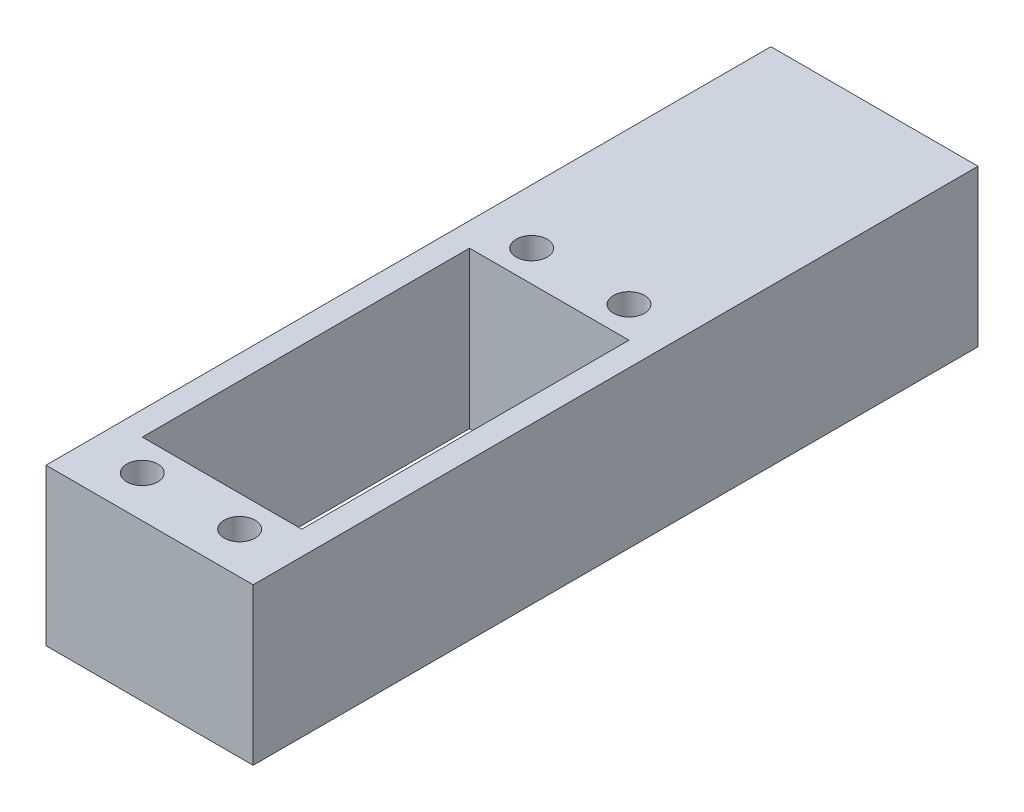
SolidWorks part; units mm, degrees
ref_plane "Front Plane" through (0, 0, 0) normal (0, 0, 1) x (1, 0, 0)
ref_plane "Top Plane" through (0, 0, 0) normal (0, 1, 0) x (1, 0, 0)
ref_plane "Right Plane" through (0, 0, 0) normal (1, 0, 0) x (0, 0, -1)
sketch "Sketch1" plane through (0, 0, 0) normal (0, 1, 0) x (1, 0, 0)
  line L0 (0, 0) -> (25.4, 0)
  line L1 (0, 0) -> (0, 88.9)
  line L2 (0, 88.9) -> (25.4, 88.9)
  line L3 (25.4, 88.9) -> (25.4, 0)
  line L4 (2.921, 8.89) -> (22.479, 8.89)
  line L5 (2.921, 8.89) -> (2.921, 49.022)
  line L6 (2.921, 49.022) -> (22.479, 49.022)
  line L7 (22.479, 49.022) -> (22.479, 8.89)
  line L8 (2.921, 49.022) -> (2.921, 52.4771) construction
  line L9 (22.479, 49.022) -> (22.479, 52.4771) construction
  line L10 (2.921, 8.89) -> (2.921, 5.5817) construction
  line L11 (22.479, 8.89) -> (22.479, 6.0014) construction
  circle A0 centre (6.731, 52.832) radius 1.905
  circle A1 centre (18.669, 52.832) radius 1.905
  circle A2 centre (6.731, 5.08) radius 1.905
  circle A3 centre (18.669, 5.08) radius 1.905
  dimension "D1" = 25.4
  dimension "D7" = 3.81
  dimension "D15" = 3.81
  dimension "D16" = 3.81
  dimension "D17" = 3.81
  dimension "D18" = 3.81
  dimension "D2" = 88.9
  dimension "D3" = 19.558
  dimension "D4" = 2.921
  dimension "D5" = 40.132
  dimension "D6" = 8.89
  dimension "D8" = 3.81
  dimension "D9" = 3.81
  dimension "D10" = 3.81
  dimension "D11" = 3.81
  dimension "D12" = 3.81
  dimension "D13" = 3.81
  dimension "D14" = 3.81
extrude "Boss-Extrude1" add sketch "Sketch1" along normal blind 19.177
